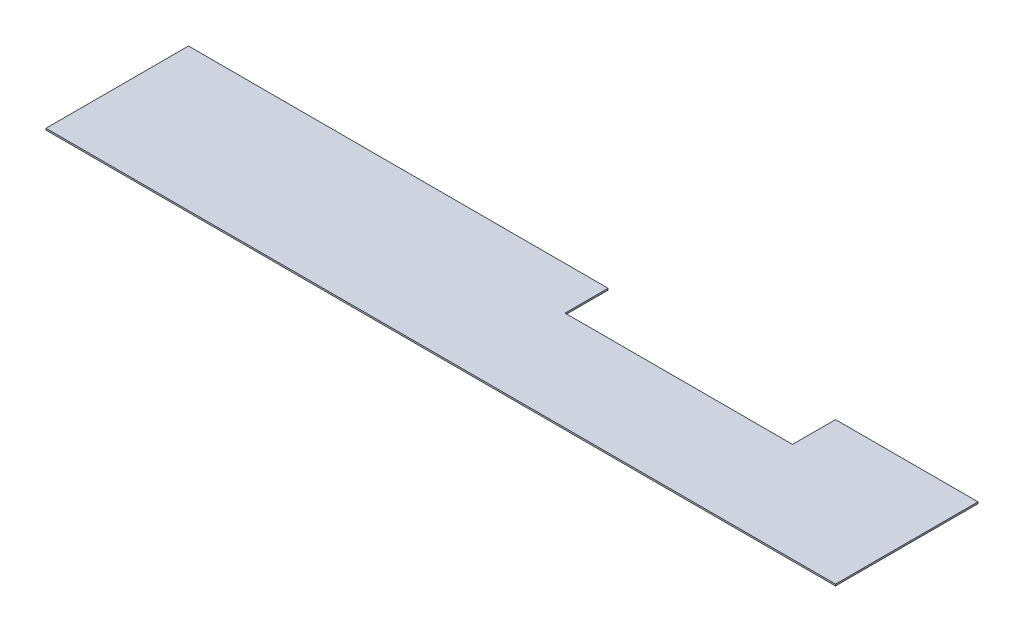
SolidWorks part; units mm, degrees
material "MDF"
ref_plane "Front Plane" through (0, 0, 0) normal (0, 0, 1) x (1, 0, 0)
ref_plane "Top Plane" through (0, 0, 0) normal (0, 1, 0) x (1, 0, 0)
ref_plane "Right Plane" through (0, 0, 0) normal (1, 0, 0) x (0, 0, -1)
sketch "Sketch1" plane through (0, 0, 0) normal (0, 1, 0) x (1, 0, 0)
  line L1 (-762, -137.5) -> (762, -137.5)
  line L2 (-762, -137.5) -> (-762, 137.5)
  line L3 (-762, 137.5) -> (762, 137.5)
  line L4 (762, -137.5) -> (762, 137.5)
  line L5 (-762, -137.5) -> (762, 137.5) construction
  line L6 (-762, 137.5) -> (762, -137.5) construction
  point P0 (0, 0)
  dimension "D1" = 1524
  dimension "D2" = 275
extrude "Boss-Extrude1" add sketch "Sketch1" along normal blind 3.175
sketch "Sketch2" plane through (0, 0, 0) normal (0, -1, 0) x (1, 0, 0)
  line L0 (762, -137.5) -> (-762, -137.5) construction
  line L1 (48, -137.5) -> (487, -137.5)
  line L2 (48, -137.5) -> (48, -54.5)
  line L3 (48, -54.5) -> (487, -54.5)
  line L4 (487, -137.5) -> (487, -54.5)
  dimension "D1" = 275
  dimension "D2" = 439
  dimension "D3" = 83
extrude "Cut-Extrude1" cut sketch "Sketch2" against normal up to next
